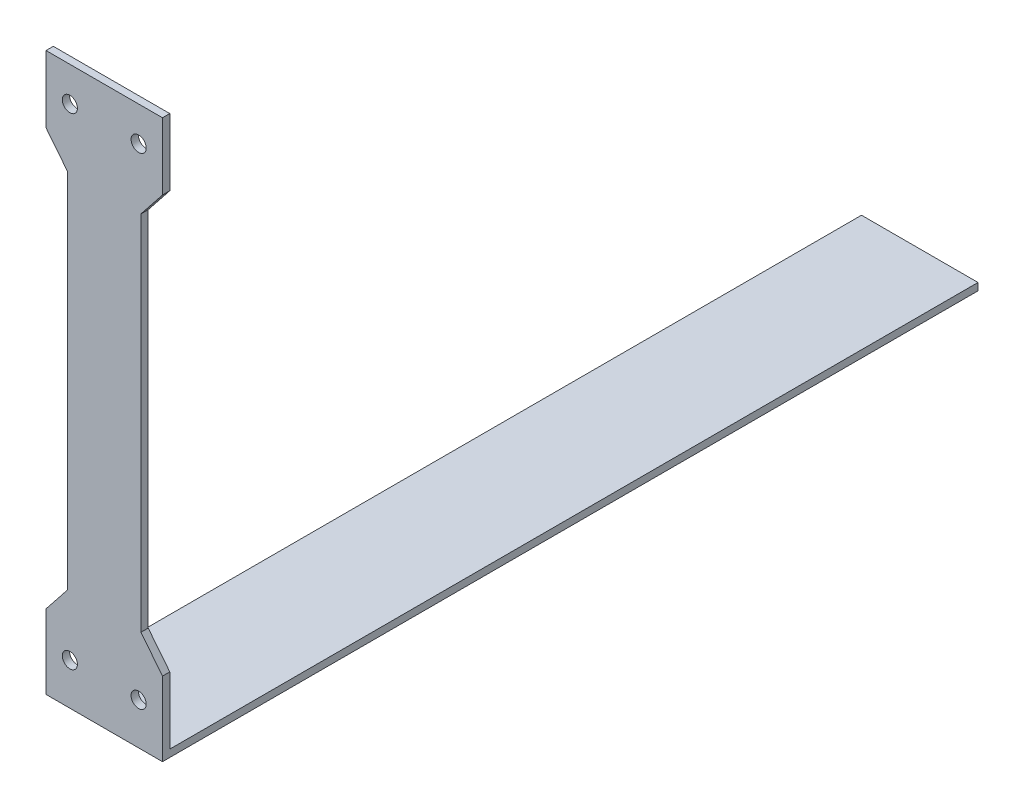
SolidWorks part; units mm, degrees
ref_plane "Front Plane" through (0, 0, 0) normal (0, 0, 1) x (1, 0, 0)
ref_plane "Top Plane" through (0, 0, 0) normal (0, 1, 0) x (1, 0, 0)
ref_plane "Right Plane" through (0, 0, 0) normal (1, 0, 0) x (0, 0, -1)
sketch "Sketch1" plane through (0, 0, 0) normal (0, 0, 1) x (1, 0, 0)
  line L0 (-117, 99.5) -> (-103.5, 116.5) construction
  line L1 (-146.5, 116.5) -> (-133, 99.5) construction
  line L2 (-133, 99.5) -> (-117, 99.5) construction
  line L3 (-117, 99.5) -> (-103.5, 116.5)
  line L4 (-146.5, 116.5) -> (-133, 99.5)
  line L5 (-133, 99.5) -> (-117, 99.5) construction
  line L6 (-250, 120) -> (0, 120) construction
  line L7 (-146.5, 120) -> (-103.5, 120)
  line L8 (0, 0) -> (-250, 0) construction
  line L9 (-103.5, 3.5) -> (-117, 20.5) construction
  line L10 (-117, 20.5) -> (-133, 20.5) construction
  line L11 (-133, 20.5) -> (-146.5, 3.5) construction
  line L12 (-103.5, 0) -> (-146.5, 0)
  line L13 (-103.5, 3.5) -> (-117, 20.5)
  line L14 (-117, 20.5) -> (-133, 20.5) construction
  line L15 (-133, 20.5) -> (-146.5, 3.5)
  line L16 (-103.5, 3.5) -> (-103.5, 0)
  line L17 (-137.7, 14.5815) -> (-137.7, 0)
  line L18 (-146.5, 3.5) -> (-146.5, 0)
  line L19 (-103.5, 116.5) -> (-103.5, 120)
  line L20 (-146.5, 116.5) -> (-146.5, 120)
  line L21 (-117, 20.5) -> (-117, 99.5)
  line L22 (-133, 99.5) -> (-133, 20.5)
  line L23 (-125, 0) -> (-125, 120) construction
  line L24 (-112.3, 14.5815) -> (-112.3, 0)
  line L25 (-137.7, 105.4185) -> (-137.7, 120)
  line L26 (-112.3, 120) -> (-112.3, 105.4185)
  arc A0 (-134.15, 112.5) -> (-130.85, 112.5) centre (-132.5, 112.5) ccw construction
  arc A1 (-130.85, 112.5) -> (-134.15, 112.5) centre (-132.5, 112.5) ccw construction
  arc A2 (-119.15, 112.5) -> (-115.85, 112.5) centre (-117.5, 112.5) ccw construction
  arc A3 (-115.85, 112.5) -> (-119.15, 112.5) centre (-117.5, 112.5) ccw construction
  arc A4 (-134.15, 112.5) -> (-130.85, 112.5) centre (-132.5, 112.5) ccw
  arc A5 (-130.85, 112.5) -> (-134.15, 112.5) centre (-132.5, 112.5) ccw
  arc A6 (-119.15, 112.5) -> (-115.85, 112.5) centre (-117.5, 112.5) ccw
  arc A7 (-115.85, 112.5) -> (-119.15, 112.5) centre (-117.5, 112.5) ccw
  arc A8 (-115.85, 7.5) -> (-119.15, 7.5) centre (-117.5, 7.5) ccw construction
  arc A9 (-119.15, 7.5) -> (-115.85, 7.5) centre (-117.5, 7.5) ccw construction
  arc A10 (-134.15, 7.5) -> (-130.85, 7.5) centre (-132.5, 7.5) ccw construction
  arc A11 (-130.85, 7.5) -> (-134.15, 7.5) centre (-132.5, 7.5) ccw construction
  arc A12 (-115.85, 7.5) -> (-119.15, 7.5) centre (-117.5, 7.5) ccw
  arc A13 (-119.15, 7.5) -> (-115.85, 7.5) centre (-117.5, 7.5) ccw
  arc A14 (-134.15, 7.5) -> (-130.85, 7.5) centre (-132.5, 7.5) ccw
  arc A15 (-130.85, 7.5) -> (-134.15, 7.5) centre (-132.5, 7.5) ccw
  dimension "D1" = 12.7
extrude "Boss-Extrude1" add sketch "Sketch1" along normal blind 1.5875 contours L24 L13 L21 L3 L19 L7 L20 L4 L22 L15 L17 L12 A15 A14 A13 A12 A7 A6 A5 A4
sketch "Sketch2" plane through (0, 0, 0) normal (0, 1, 0) x (1, 0, 0)
  line L0 (-112.3, -1.5875) -> (-112.3, 176.2125)
  line L1 (-112.3, 176.2125) -> (-137.7, 176.2125)
  line L2 (-137.7, 176.2125) -> (-137.7, -1.5875)
  line L3 (-137.7, -1.5875) -> (-112.3, -1.5875) construction
  line L5 (-137.7, -1.5875) -> (-112.3, -1.5875)
  dimension "D1" = 177.8
extrude "Boss-Extrude2" add sketch "Sketch2" against normal blind 1.5875
